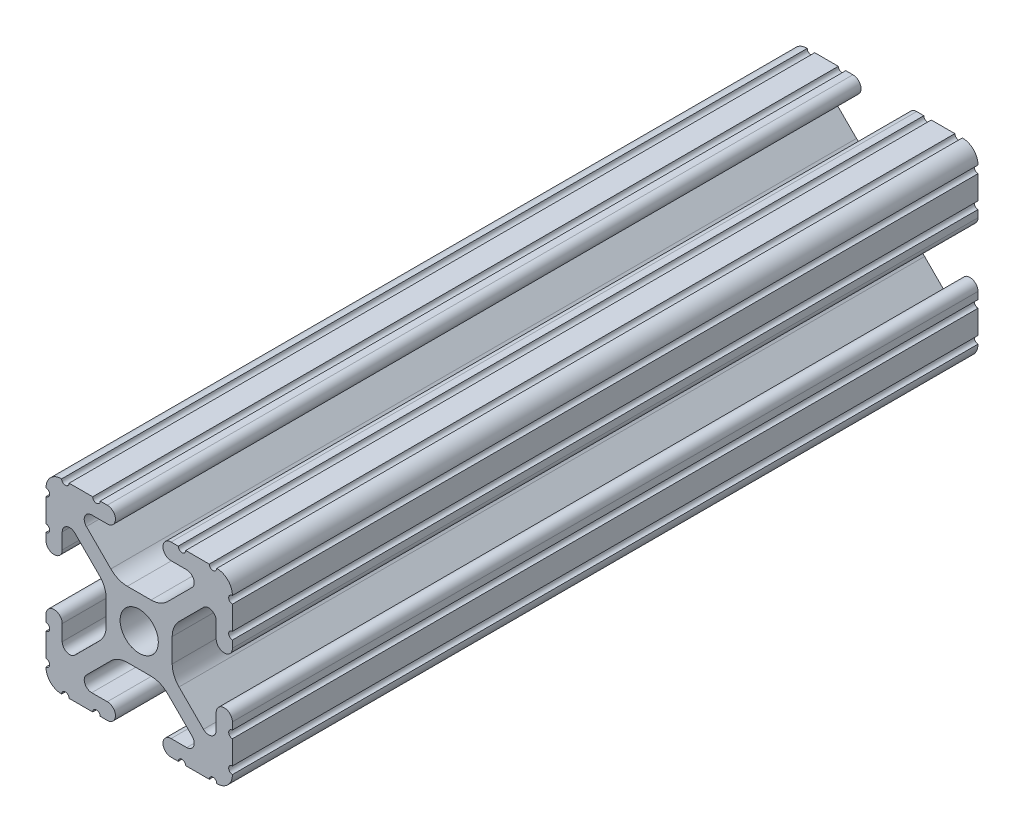
SolidWorks part; units mm, degrees
ref_plane "Front Plane" through (0, 0, 0) normal (0, 0, 1) x (1, 0, 0)
ref_plane "Top Plane" through (0, 0, 0) normal (0, 1, 0) x (1, 0, 0)
ref_plane "Right Plane" through (0, 0, 0) normal (1, 0, 0) x (0, 0, -1)
ref_plane "Plane1" through (0, 0, -101.6) normal (0, 0, -1) x (-1, 0, 0)
sketch "Sketch1" plane through (0, 0, -101.6) normal (0, 0, -1) x (-1, 0, 0)
  line L0 (12.7, -9.5504) -> (12.7, -6.3331)
  line L1 (12.7, -5.3171) -> (12.7, -4.3434)
  line L2 (10.4902, -4.3434) -> (10.4902, -6.4748)
  line L3 (8.7558, -7.1932) -> (5.4257, -3.8632)
  line L4 (4.4958, -1.6181) -> (4.4958, 1.6181)
  line L5 (5.4257, 3.8632) -> (8.7558, 7.1932)
  line L6 (10.4902, 6.4748) -> (10.4902, 4.3434)
  line L7 (12.7, 4.3434) -> (12.7, 5.3171)
  line L8 (12.7, 6.3331) -> (12.7, 9.5504)
  line L9 (9.5504, 12.7) -> (6.3331, 12.7)
  line L10 (5.3171, 12.7) -> (4.3434, 12.7)
  line L11 (4.3434, 10.4902) -> (6.4748, 10.4902)
  line L12 (7.1932, 8.7558) -> (3.8632, 5.4257)
  line L13 (1.6181, 4.4958) -> (-1.6181, 4.4958)
  line L14 (-3.8632, 5.4257) -> (-7.1932, 8.7558)
  line L15 (-6.4748, 10.4902) -> (-4.3434, 10.4902)
  line L16 (-4.3434, 12.7) -> (-5.3171, 12.7)
  line L17 (-6.3331, 12.7) -> (-9.5504, 12.7)
  line L18 (-12.7, 9.5504) -> (-12.7, 6.3331)
  line L19 (-12.7, 5.3171) -> (-12.7, 4.3434)
  line L20 (-10.4902, 4.3434) -> (-10.4902, 6.4748)
  line L21 (-8.7558, 7.1932) -> (-5.4257, 3.8632)
  line L22 (-4.4958, 1.6181) -> (-4.4958, -1.6181)
  line L23 (-5.4257, -3.8632) -> (-8.7558, -7.1932)
  line L24 (-10.4902, -6.4748) -> (-10.4902, -4.3434)
  line L25 (-12.7, -4.3434) -> (-12.7, -5.3171)
  line L26 (-12.7, -6.3331) -> (-12.7, -9.5504)
  line L27 (-9.5504, -12.7) -> (-6.3331, -12.7)
  line L28 (-5.3171, -12.7) -> (-4.3434, -12.7)
  line L29 (-4.3434, -10.4902) -> (-6.4748, -10.4902)
  line L30 (-7.1932, -8.7558) -> (-3.8632, -5.4257)
  line L31 (-1.6181, -4.4958) -> (1.6181, -4.4958)
  line L32 (3.8632, -5.4257) -> (7.1932, -8.7558)
  line L33 (6.4748, -10.4902) -> (4.3434, -10.4902)
  line L34 (4.3434, -12.7) -> (5.3171, -12.7)
  line L35 (6.3331, -12.7) -> (9.5504, -12.7)
  arc A0 (12.6998, -10.5664) -> (12.7, -9.5504) centre (12.7, -10.0584) cw
  arc A1 (12.7, -6.3331) -> (12.7, -5.3171) centre (12.7, -5.8251) cw
  arc A2 (12.7, -4.3434) -> (10.4902, -4.3434) centre (11.5951, -4.3434) ccw
  arc A3 (10.4902, -6.4748) -> (8.7558, -7.1932) centre (9.4742, -6.4748) cw
  arc A4 (5.4257, -3.8632) -> (4.4958, -1.6181) centre (7.6708, -1.6181) cw
  arc A5 (4.4958, 1.6181) -> (5.4257, 3.8632) centre (7.6708, 1.6181) cw
  arc A6 (8.7558, 7.1932) -> (10.4902, 6.4748) centre (9.4742, 6.4748) cw
  arc A7 (10.4902, 4.3434) -> (12.7, 4.3434) centre (11.5951, 4.3434) ccw
  arc A8 (12.7, 5.3171) -> (12.7, 6.3331) centre (12.7, 5.8251) cw
  arc A9 (12.7, 9.5504) -> (12.6998, 10.5664) centre (12.7, 10.0584) cw
  arc A10 (12.6998, 10.5664) -> (10.5664, 12.6998) centre (10.5918, 10.5918) ccw
  arc A11 (10.5664, 12.6998) -> (9.5504, 12.7) centre (10.0584, 12.7) cw
  arc A12 (6.3331, 12.7) -> (5.3171, 12.7) centre (5.8251, 12.7) cw
  arc A13 (4.3434, 12.7) -> (4.3434, 10.4902) centre (4.3434, 11.5951) ccw
  arc A14 (6.4748, 10.4902) -> (7.1932, 8.7558) centre (6.4748, 9.4742) cw
  arc A15 (3.8632, 5.4257) -> (1.6181, 4.4958) centre (1.6181, 7.6708) cw
  arc A16 (-1.6181, 4.4958) -> (-3.8632, 5.4257) centre (-1.6181, 7.6708) cw
  arc A17 (-7.1932, 8.7558) -> (-6.4748, 10.4902) centre (-6.4748, 9.4742) cw
  arc A18 (-4.3434, 10.4902) -> (-4.3434, 12.7) centre (-4.3434, 11.5951) ccw
  arc A19 (-5.3171, 12.7) -> (-6.3331, 12.7) centre (-5.8251, 12.7) cw
  arc A20 (-9.5504, 12.7) -> (-10.5664, 12.6998) centre (-10.0584, 12.7) cw
  arc A21 (-10.5664, 12.6998) -> (-12.6998, 10.5664) centre (-10.5918, 10.5918) ccw
  arc A22 (-12.6998, 10.5664) -> (-12.7, 9.5504) centre (-12.7, 10.0584) cw
  arc A23 (-12.7, 6.3331) -> (-12.7, 5.3171) centre (-12.7, 5.8251) cw
  arc A24 (-12.7, 4.3434) -> (-10.4902, 4.3434) centre (-11.5951, 4.3434) ccw
  arc A25 (-10.4902, 6.4748) -> (-8.7558, 7.1932) centre (-9.4742, 6.4748) cw
  arc A26 (-5.4257, 3.8632) -> (-4.4958, 1.6181) centre (-7.6708, 1.6181) cw
  arc A27 (-4.4958, -1.6181) -> (-5.4257, -3.8632) centre (-7.6708, -1.6181) cw
  arc A28 (-8.7558, -7.1932) -> (-10.4902, -6.4748) centre (-9.4742, -6.4748) cw
  arc A29 (-10.4902, -4.3434) -> (-12.7, -4.3434) centre (-11.5951, -4.3434) ccw
  arc A30 (-12.7, -5.3171) -> (-12.7, -6.3331) centre (-12.7, -5.8251) cw
  arc A31 (-12.7, -9.5504) -> (-12.6998, -10.5664) centre (-12.7, -10.0584) cw
  arc A32 (-12.6998, -10.5664) -> (-10.5664, -12.6998) centre (-10.5918, -10.5918) ccw
  arc A33 (-10.5664, -12.6998) -> (-9.5504, -12.7) centre (-10.0584, -12.7) cw
  arc A34 (-6.3331, -12.7) -> (-5.3171, -12.7) centre (-5.8251, -12.7) cw
  arc A35 (-4.3434, -12.7) -> (-4.3434, -10.4902) centre (-4.3434, -11.5951) ccw
  arc A36 (-6.4748, -10.4902) -> (-7.1932, -8.7558) centre (-6.4748, -9.4742) cw
  arc A37 (-3.8632, -5.4257) -> (-1.6181, -4.4958) centre (-1.6181, -7.6708) cw
  arc A38 (1.6181, -4.4958) -> (3.8632, -5.4257) centre (1.6181, -7.6708) cw
  arc A39 (7.1932, -8.7558) -> (6.4748, -10.4902) centre (6.4748, -9.4742) cw
  arc A40 (4.3434, -10.4902) -> (4.3434, -12.7) centre (4.3434, -11.5951) ccw
  arc A41 (5.3171, -12.7) -> (6.3331, -12.7) centre (5.8251, -12.7) cw
  arc A42 (9.5504, -12.7) -> (10.5664, -12.6998) centre (10.0584, -12.7) cw
  arc A43 (10.5664, -12.6998) -> (12.6998, -10.5664) centre (10.5918, -10.5918) ccw
  circle A44 centre (0, 0) radius 2.6035
extrude "Boss-Extrude1" add sketch "Sketch1" against normal blind 101.6
